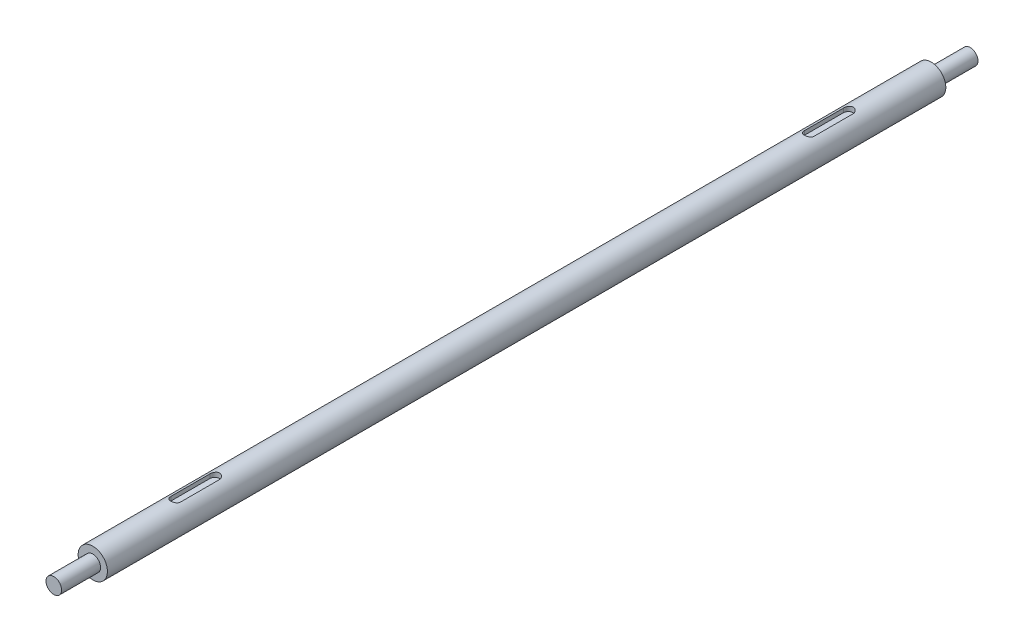
SolidWorks part; units mm, degrees
ref_plane "前视基准面" through (0, 0, 0) normal (0, 0, 1) x (1, 0, 0)
ref_plane "上视基准面" through (0, 0, 0) normal (0, 1, 0) x (1, 0, 0)
ref_plane "右视基准面" through (0, 0, 0) normal (1, 0, 0) x (0, 0, -1)
sketch "草图1" plane through (0, 0, 0) normal (0, 0, 1) x (1, 0, 0)
  circle A0 centre (0, 0) radius 7.5
  dimension "D1" = 15
extrude "凸台-拉伸1" add sketch "草图1" along normal mid plane 430
ref_plane "基准面1" through (0, 7.5, 0) normal (0, 1, 0) x (1, 0, 0)
sketch "草图2" plane through (0, 7.5, 0) normal (0, 1, 0) x (1, 0, 0)
  line L0 (0, 0) -> (-39.1284, 0) construction
  line L13 (0, -152.5) -> (0, -172.5) construction
  line L14 (-2, 0) -> (2, 0) construction
  line L19 (0, -172.5) -> (0, -152.5) construction
  line L20 (-2.5, -152.5) -> (2.5, -152.5) construction
  line L21 (-2.5, 152.5) -> (2.5, 152.5) construction
  line L26 (2.5, -152.5) -> (2.5, -172.5)
  line L27 (-2.5, -152.5) -> (-2.5, -172.5)
  line L28 (0, 172.5) -> (0, 152.5) construction
  line L29 (0, 152.5) -> (0, 172.5) construction
  line L30 (2.5, 152.5) -> (2.5, 172.5)
  line L31 (-2.5, 152.5) -> (-2.5, 172.5)
  arc A0 (2.5, -152.5) -> (-2.5, -152.5) centre (0, -152.5) ccw
  arc A1 (-2.5, -172.5) -> (2.5, -172.5) centre (0, -172.5) ccw
  arc A2 (2.5, 152.5) -> (-2.5, 152.5) centre (0, 152.5) cw
  arc A3 (-2.5, 172.5) -> (2.5, 172.5) centre (0, 172.5) cw
  point P0 (0, 0)
  point P1 (0, -162.5)
  point P12 (0, 162.5)
  dimension "D2" = 2.5
  dimension "D1" = 20
  dimension "D3" = 162.5
extrude "切除-拉伸1" cut sketch "草图2" against normal blind 2.5
sketch "草图3" plane through (0, 0, 215) normal (0, 0, 1) x (1, 0, 0)
  circle A0 centre (0, 0) radius 4
  dimension "D1" = 8
extrude "凸台-拉伸2" add sketch "草图3" along normal blind 20
mirror "镜向1" about plane through (0, 0, 0) normal (0, 0, 1) of "凸台-拉伸2"
